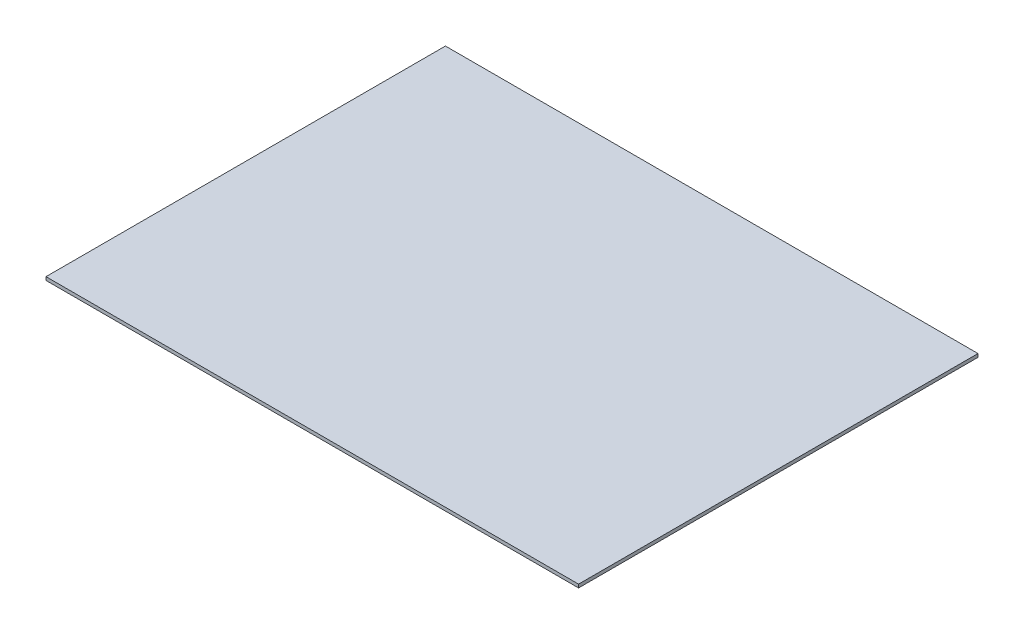
SolidWorks part; units mm, degrees
ref_plane "Front Plane" through (0, 0, 0) normal (0, 0, 1) x (1, 0, 0)
ref_plane "Top Plane" through (0, 0, 0) normal (0, 1, 0) x (1, 0, 0)
ref_plane "Right Plane" through (0, 0, 0) normal (1, 0, 0) x (0, 0, -1)
sketch "Sketch2" plane through (0, 0, 0) normal (0, 1, 0) x (1, 0, 0)
  line L1 (-80, 60) -> (80, 60)
  line L2 (-80, 60) -> (-80, -60)
  line L3 (-80, -60) -> (80, -60)
  line L4 (80, 60) -> (80, -60)
  line L5 (-80, 60) -> (80, -60) construction
  line L6 (-80, -60) -> (80, 60) construction
  point P0 (0, 0)
  dimension "D1" = 160
  dimension "D2" = 120
extrude "Boss-Extrude1" add sketch "Sketch2" along normal blind 1
sketch "Sketch3" plane through (0, 0, 0) normal (0, -1, 0) x (1, 0, 0)
  line L0 (-65, 60) -> (-65, -60) construction
  line L1 (-80, 60) -> (80, 60) construction
  line L2 (80, -60) -> (-80, -60) construction
  line L3 (65, 60) -> (65, -60) construction
  line L4 (-80, -60) -> (-80, 60) construction
  line L5 (80, 60) -> (80, -60) construction
  dimension "D1" = 15
  dimension "D2" = 15
